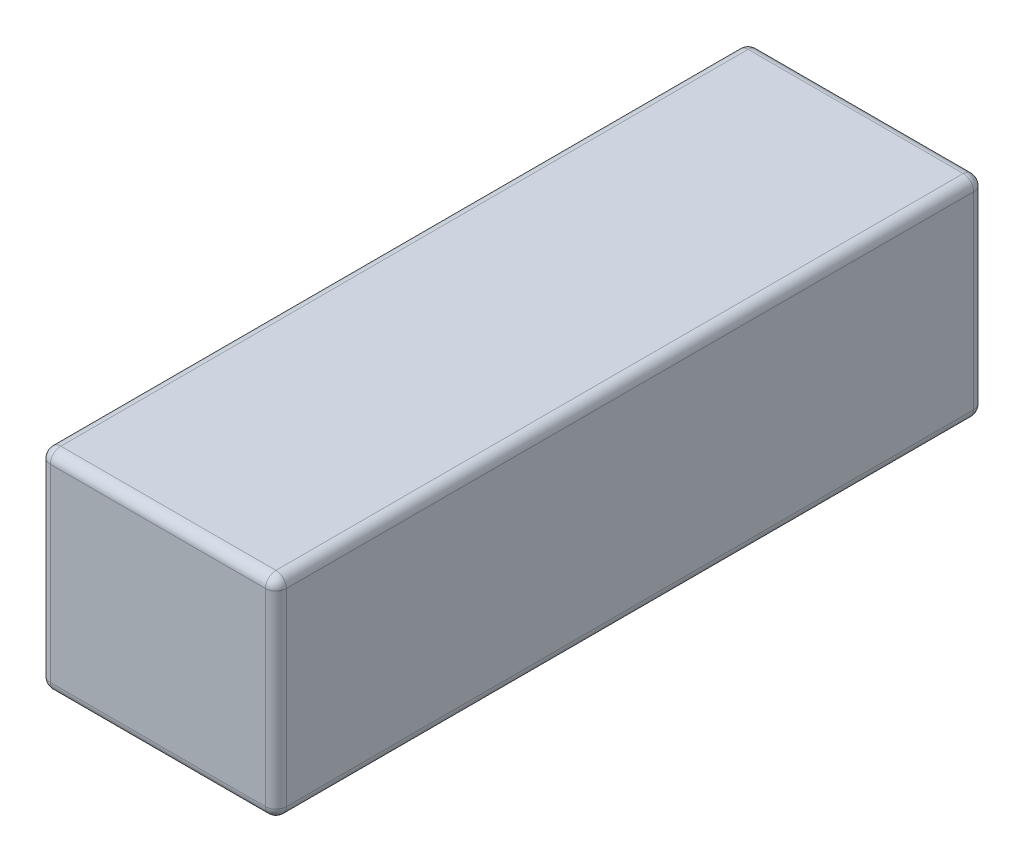
SolidWorks part; units mm, degrees
ref_plane "Front Plane" through (0, 0, 0) normal (0, 0, 1) x (1, 0, 0)
ref_plane "Top Plane" through (0, 0, 0) normal (0, 1, 0) x (1, 0, 0)
ref_plane "Right Plane" through (0, 0, 0) normal (1, 0, 0) x (0, 0, -1)
sketch "Sketch1" plane through (0, 0, 0) normal (0, 0, 1) x (1, 0, 0)
  line L1 (-22.5, -20) -> (22.5, -20)
  line L2 (-22.5, -20) -> (-22.5, 20)
  line L3 (-22.5, 20) -> (22.5, 20)
  line L4 (22.5, -20) -> (22.5, 20)
  line L5 (-22.5, -20) -> (22.5, 20) construction
  line L6 (-22.5, 20) -> (22.5, -20) construction
  point P0 (0, 0)
  dimension "D1" = 40
  dimension "D2" = 45
extrude "Boss-Extrude1" add sketch "Sketch1" along normal blind 135
fillet "Fillet1" radius 2 12 edges at (-22.5, -20, 67.5) (-22.5, 20, 67.5) (0, 20, 0) (-22.5, 0, 0) (0, -20, 0) (0, -20, 135) (-22.5, 0, 135) (0, 20, 135) (22.5, -20, 67.5) (22.5, 0, 135) (22.5, 20, 67.5) (22.5, 0, 0)
